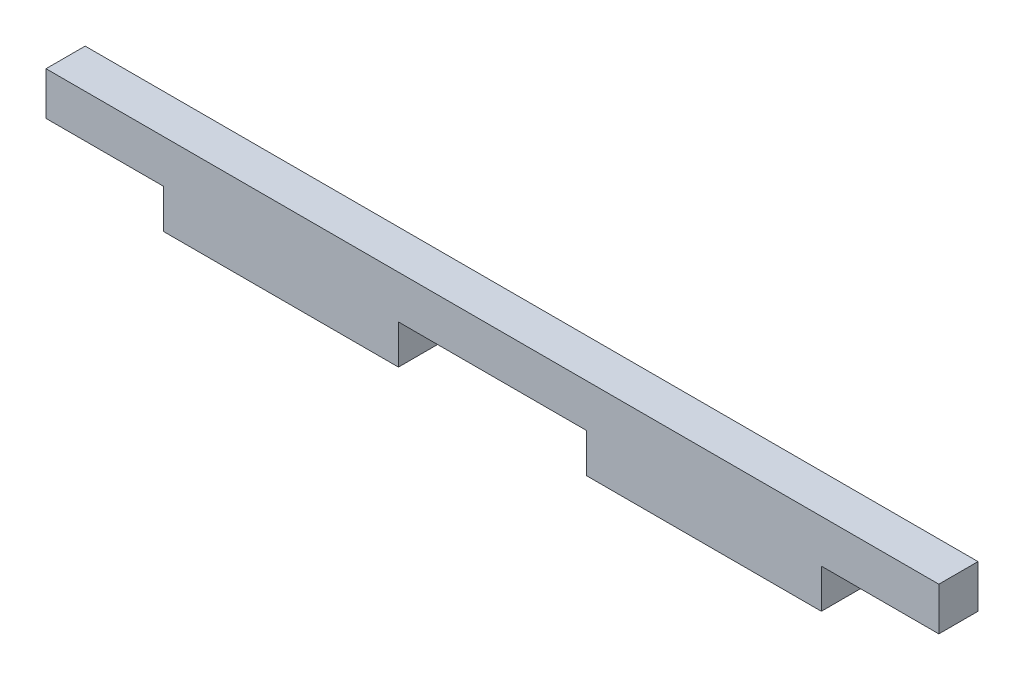
SolidWorks part; units mm, degrees
ref_plane "前视基准面" through (0, 0, 0) normal (0, 0, 1) x (1, 0, 0)
ref_plane "上视基准面" through (0, 0, 0) normal (0, 1, 0) x (1, 0, 0)
ref_plane "右视基准面" through (0, 0, 0) normal (1, 0, 0) x (0, 0, -1)
sketch "草图1" plane through (0, 0, 0) normal (0, 0, 1) x (1, 0, 0)
  line L1 (0, 0) -> (-114, 0)
  line L2 (0, 0) -> (0, 5.5)
  line L3 (0, 5.5) -> (-114, 5.5)
  line L4 (-114, 0) -> (-114, 5.5)
  line L5 (-99, 0) -> (-69, 0)
  line L6 (-99, 0) -> (-99, -5)
  line L7 (-99, -5) -> (-69, -5)
  line L8 (-69, 0) -> (-69, -5)
  line L9 (-45, 0) -> (-15, 0)
  line L10 (-45, 0) -> (-45, -5)
  line L11 (-45, -5) -> (-15, -5)
  line L12 (-15, 0) -> (-15, -5)
  point P13 (0, 2.75)
  dimension "D1" = 5
  dimension "D2" = 30
  dimension "D3" = 5
  dimension "D4" = 30
  dimension "D5" = 5.5
  dimension "D6" = 114
  dimension "D7" = 15
  dimension "D8" = 15
extrude "凸台-拉伸1" add sketch "草图1" along normal blind 5 contours L4 L1 L2 L3 | L8 L1 L6 L7 | L12 L1 L10 L11
